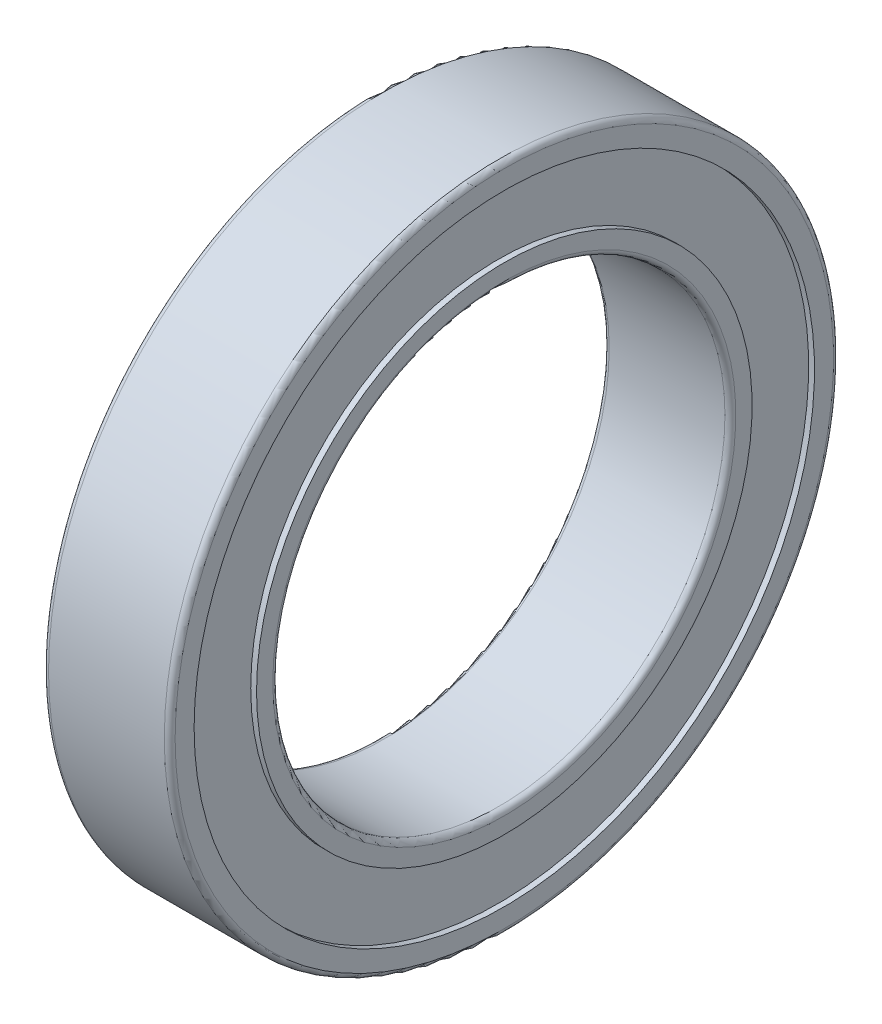
SolidWorks part; units mm, degrees
material "SUJ2"
ref_plane "Front Plane" through (0, 0, 0) normal (0, 0, 1) x (1, 0, 0)
ref_plane "Top Plane" through (0, 0, 0) normal (0, 1, 0) x (1, 0, 0)
ref_plane "Right Plane" through (0, 0, 0) normal (1, 0, 0) x (0, 0, -1)
sketch "Sketch1" plane through (0, 0, 0) normal (0, 0, 1) x (1, 0, 0)
  line L0 (0, 0) -> (7, 0) construction
  line L1 (0, 12.5) -> (7, 12.5)
  line L2 (0, 18.5) -> (7, 18.5)
  line L3 (0, 18.5) -> (0, 17.15)
  line L4 (0, 17.15) -> (0.32, 17.15)
  line L5 (7, 18.5) -> (7, 17.15)
  line L6 (0.32, 17.15) -> (0.32, 13.7)
  line L7 (0.32, 13.7) -> (0, 13.7)
  line L8 (0, 13.7) -> (0, 12.5)
  line L9 (7, 17.15) -> (6.68, 17.15)
  line L10 (6.68, 17.15) -> (6.68, 13.7)
  line L11 (6.68, 13.7) -> (7, 13.7)
  line L12 (7, 13.7) -> (7, 12.5)
  dimension "D" = 37
  dimension "B" = 7
  dimension "D_s" = 25
  dimension "MSM_1" = 34.3
  dimension "MSM_2" = 27.4
  dimension "MSM_3" = 0.32
revolve "Revolve1" add sketch "Sketch1" angle 360 about L0
fillet "Fillet1" radius 0.3 2 edges at (7, 0, 18.5) (0, 0, 18.5)
fillet "Fillet2" radius 0.3 2 edges at (7, 0, 12.5) (0, 0, 12.5)
